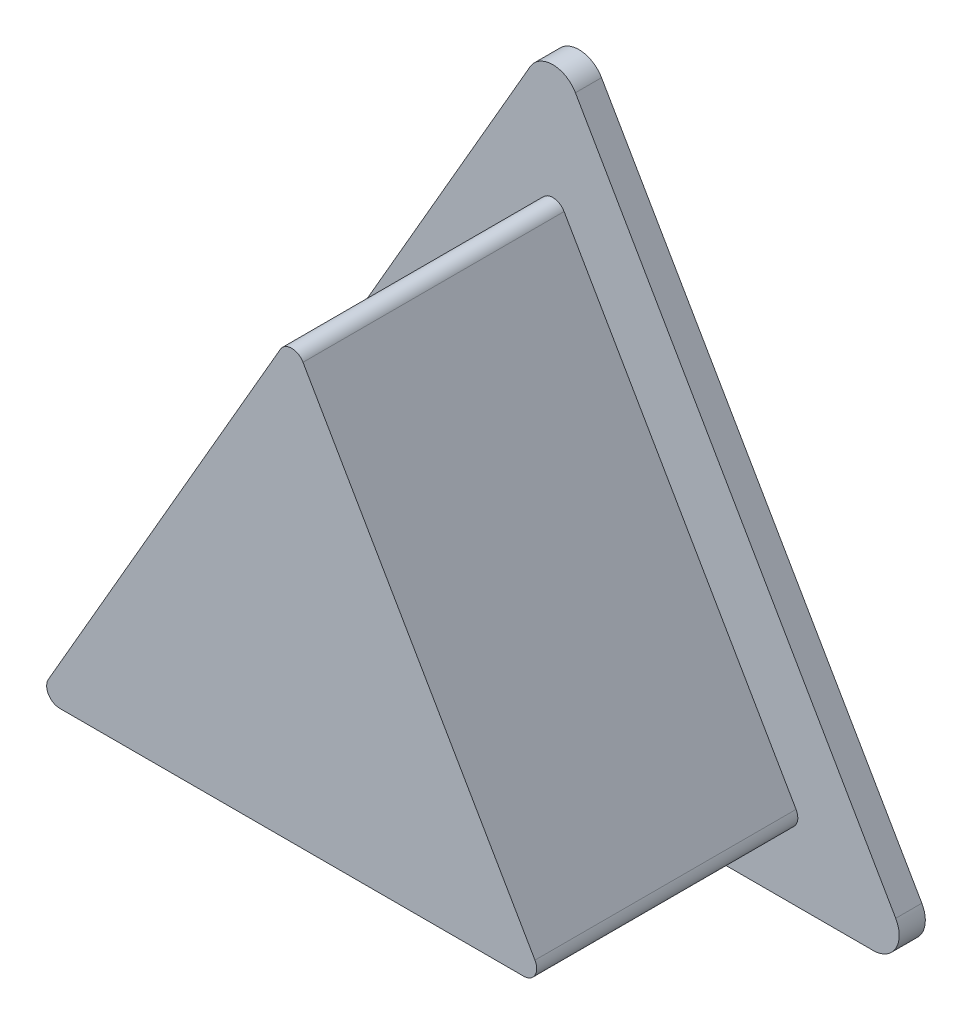
SolidWorks part; units mm, degrees
ref_plane "Front Plane" through (0, 0, 0) normal (0, 0, 1) x (1, 0, 0)
ref_plane "Top Plane" through (0, 0, 0) normal (0, 1, 0) x (1, 0, 0)
ref_plane "Right Plane" through (0, 0, 0) normal (1, 0, 0) x (0, 0, -1)
sketch "Sketch1" plane through (0, 0, 0) normal (0, 0, 1) x (1, 0, 0)
  line L0 (-4.875, 0) -> (4.875, 0) construction
  line L1 (0, 5.6292) -> (-4.875, -2.8146)
  line L2 (-4.875, -2.8146) -> (4.875, -2.8146)
  line L3 (4.875, -2.8146) -> (0, 5.6292)
  circle A0 centre (0, 0) radius 2.8146 construction
  dimension "D1" = 9.75
  dimension "D2" = 2.8146
  dimension "D3" = 2.8146
extrude "Boss-Extrude1" add sketch "Sketch1" along normal blind 5
sketch "Sketch2" plane through (0, 0, 0) normal (0, 0, -1) x (-1, 0, 0)
  line L0 (-7, 0) -> (7, 0) construction
  line L1 (0, 8.0829) -> (-7, -4.0415)
  line L2 (-7, -4.0415) -> (7, -4.0415)
  line L3 (7, -4.0415) -> (0, 8.0829)
  line L4 (0, 0) -> (0, 8.0829) construction
  circle A0 centre (0, 0) radius 4.0415 construction
  dimension "D1" = 14
extrude "Boss-Extrude2" add sketch "Sketch2" along normal blind 0.5
fillet "Fillet1" radius 0.5 3 edges at (7, -4.0415, -0.25) (-7, -4.0415, -0.25) (0, 8.0829, -0.25)
fillet "Fillet2" radius 0.25 3 edges at (4.875, -2.8146, 2.5) (0, 5.6292, 2.5) (-4.875, -2.8146, 2.5)
sketch "Sketch3" plane through (0, 0, -0.5) normal (0, 0, -1) x (-1, 0, 0)
  line L0 (-6.134, -4.0415) -> (6.134, -4.0415) construction
  circle A0 centre (0, 0) radius 1.75
  arc A2 (0.2165, 5.2542) -> (-0.2165, 5.2542) centre (0, 5.1292) ccw construction
  arc A3 (0.433, 7.3329) -> (-0.433, 7.3329) centre (0, 7.0829) ccw construction
  point P6 (0, 5.3792)
  point P10 (0, 7.5829)
  dimension "D1" = 3.5
  dimension "D3" = 2.2037
extrude "Cut-Extrude1" cut sketch "Sketch3" against normal blind 0.75
